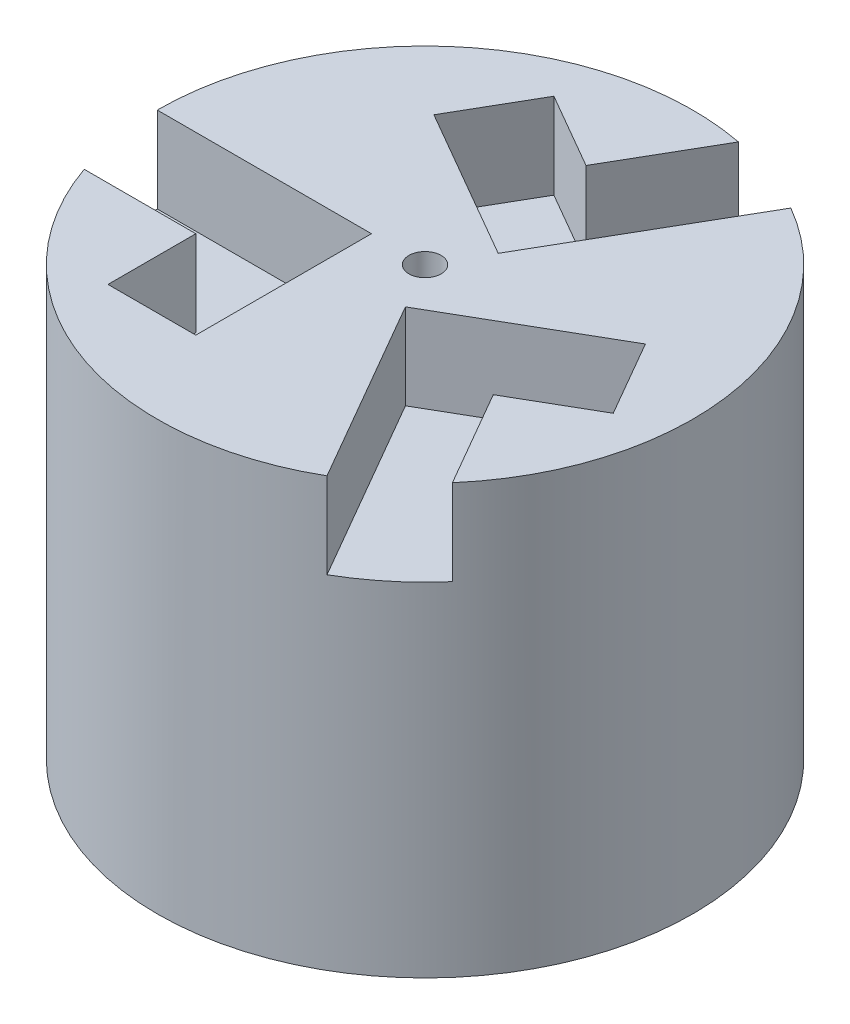
SolidWorks part; units mm, degrees
ref_plane "Front Plane" through (0, 0, 0) normal (0, 0, 1) x (1, 0, 0)
ref_plane "Top Plane" through (0, 0, 0) normal (0, 1, 0) x (1, 0, 0)
ref_plane "Right Plane" through (0, 0, 0) normal (1, 0, 0) x (0, 0, -1)
sketch "Sketch1" plane through (0, 0, 0) normal (0, 1, 0) x (1, 0, 0)
  circle A0 centre (0, 0) radius 25
  dimension "D1" = 50
extrude "Boss-Extrude1" add sketch "Sketch1" along normal blind 40
sketch "Sketch2" plane through (0, 40, 0) normal (0, 1, 0) x (1, 0, 0)
  line L0 (-25, 0) -> (-5, 0)
  line L1 (-5, 0) -> (-5, -16.4)
  line L2 (-5, -16.4) -> (-13.2, -16.4)
  line L3 (-13.2, -16.4) -> (-13.2, -8.2)
  line L4 (-13.2, -8.2) -> (-23.6169, -8.2)
  circle A0 centre (0, 0) radius 25 construction
  arc A1 (-25, 0) -> (-23.6169, -8.2) centre (0, 0) ccw
  dimension "D1" = 8.2
  dimension "D2" = 8.2
  dimension "D3" = 8.2
  dimension "D4" = 5
extrude "Cut-Extrude1" cut sketch "Sketch2" against normal blind 8
pattern_circular "CirPattern1" count 3 over 360 about axis through (0, 0, 0) along (0, 1, 0) of "Cut-Extrude1"
sketch "Sketch7" plane through (0, 0, 0) normal (0, -1, 0) x (1, 0, 0)
  circle A0 centre (0, 0) radius 15.1
  dimension "D1" = 30.2
extrude "Cut-Extrude3" cut sketch "Sketch7" against normal blind 8.7
sketch "Sketch8" plane through (0, 8.7, 0) normal (0, -1, 0) x (1, 0, 0)
  circle A0 centre (0, 0) radius 1.5
  dimension "D1" = 3
extrude "Cut-Extrude4" cut sketch "Sketch8" against normal through all
equation "\"D3@Sketch2\"=\"D1@Sketch2\""
equation "\"D2@Sketch2\"=\"D1@Sketch2\""
